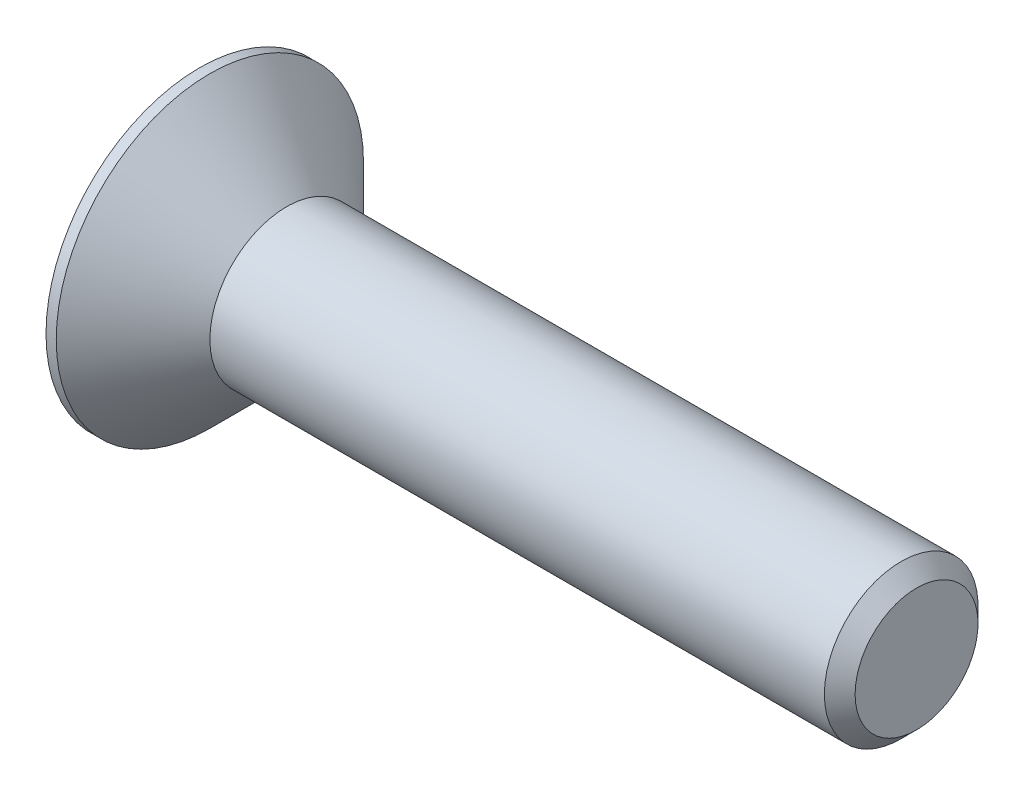
SolidWorks part; units mm, degrees
ref_plane "Plan de face" through (0, 0, 0) normal (0, 0, 1) x (1, 0, 0)
ref_plane "Plan de dessus" through (0, 0, 0) normal (0, 1, 0) x (1, 0, 0)
ref_plane "Plan de droite" through (0, 0, 0) normal (1, 0, 0) x (0, 0, -1)
sketch "Esquisse1" plane through (0, 0, 0) normal (0, 0, 1) x (1, 0, 0)
  line L0 (0, 0) -> (14, 0)
  line L1 (14, 0) -> (14, 1.5)
  line L2 (14, 1.5) -> (1.7, 1.5)
  line L3 (1.7, 1.5) -> (0.2, 3)
  line L4 (0, 3) -> (0, 0)
  line L5 (0, 3) -> (0.2, 3)
  dimension "D1" = 1.5
  dimension "D2" = 3
  dimension "D3" = 45
  dimension "D4" = 1.7
  dimension "D5" = 14
revolve "Révolution1" add sketch "Esquisse1" angle 360 about L0
chamfer "Chanfrein1" distance 0.3 angle 45 1 edges at (14, 0, 1.5)
sketch "Esquisse2" plane through (0, 0, 0) normal (-1, 0, 0) x (0, 0, 1)
  line L1 (0.5774, -1) -> (1.1547, 0)
  line L2 (1.1547, 0) -> (0.5774, 1)
  line L3 (0.5774, 1) -> (-0.5774, 1)
  line L4 (-0.5774, 1) -> (-1.1547, 0)
  line L5 (-1.1547, 0) -> (-0.5774, -1)
  line L6 (-0.5774, -1) -> (0.5774, -1)
  circle A0 centre (0, 0) radius 1 construction
  dimension "D1" = 2
extrude "Enlèv. mat.-Extru.1" cut sketch "Esquisse2" against normal blind 0.75
